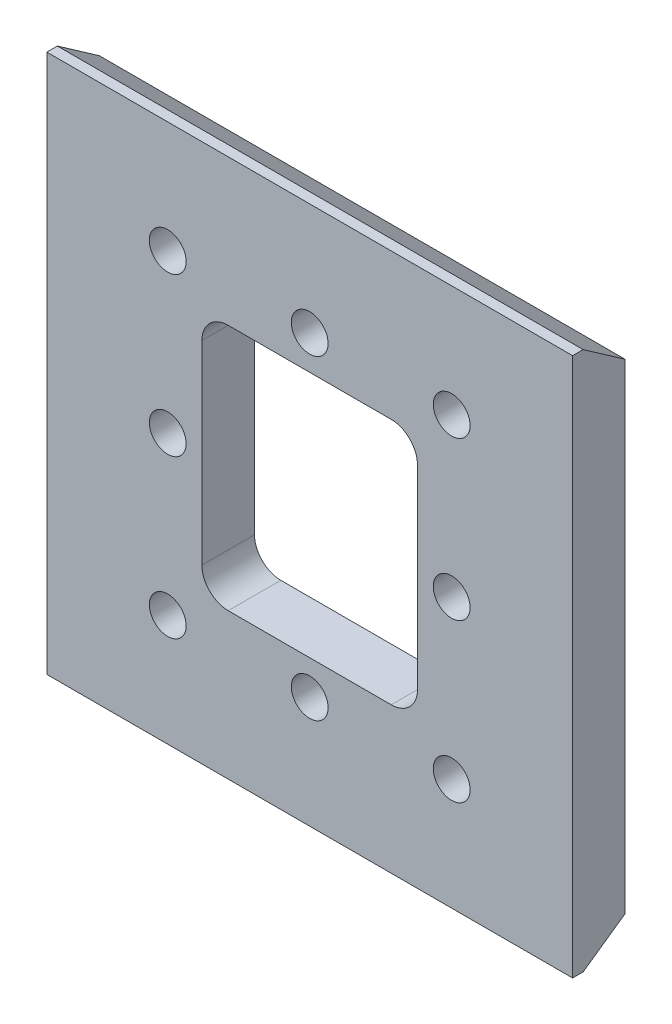
SolidWorks part; units mm, degrees
ref_plane "前视基准面" through (0, 0, 0) normal (0, 0, 1) x (1, 0, 0)
ref_plane "上视基准面" through (0, 0, 0) normal (0, 1, 0) x (1, 0, 0)
ref_plane "右视基准面" through (0, 0, 0) normal (1, 0, 0) x (0, 0, -1)
sketch "草图1" plane through (0, 0, 0) normal (0, 0, 1) x (1, 0, 0)
  line L1 (-100, 102.5) -> (100, 102.5)
  line L2 (-100, 102.5) -> (-100, -102.5)
  line L3 (-100, -102.5) -> (100, -102.5)
  line L4 (100, 102.5) -> (100, -102.5)
  line L5 (-100, 102.5) -> (100, -102.5) construction
  line L6 (-100, -102.5) -> (100, 102.5) construction
  point P0 (0, 0)
  dimension "D1" = 200
  dimension "D2" = 205
extrude "凸台-拉伸1" add sketch "草图1" along normal blind 20
sketch "草图2" plane through (0, 0, 20) normal (0, 0, 1) x (1, 0, 0)
  line L0 (0, 0) -> (128.579, 0) construction
  line L1 (0, 0) -> (0, 91.0919) construction
  line L5 (-31, 47) -> (31, 47)
  line L6 (-41, 37) -> (-41, -37)
  line L7 (-31, -47) -> (31, -47)
  line L8 (41, 37) -> (41, -37)
  line L9 (-41, 47) -> (41, -47) construction
  line L10 (-41, -47) -> (41, 47) construction
  circle A0 centre (-54, 60) radius 7
  circle A1 centre (0, 60) radius 7
  circle A2 centre (-54, 0) radius 7
  circle A3 centre (54, 0) radius 7
  circle A4 centre (54, 60) radius 7
  circle A5 centre (-54, -60) radius 7
  circle A6 centre (0, -60) radius 7
  circle A7 centre (54, -60) radius 7
  arc A8 (-41, -37) -> (-31, -47) centre (-31, -37) ccw
  arc A9 (31, -47) -> (41, -37) centre (31, -37) ccw
  arc A10 (31, 47) -> (41, 37) centre (31, 37) cw
  arc A11 (-31, 47) -> (-41, 37) centre (-31, 37) ccw
  dimension "D1" = 54
  dimension "D2" = 60
  dimension "D3" = 94
  dimension "D5" = 10
  dimension "D6" = 14
  dimension "D7" = 14
  dimension "D8" = 14
  dimension "D4" = 82
extrude "切除-拉伸1" cut sketch "草图2" against normal through all
sketch "草图3" plane through (-100, 0, 0) normal (-1, 0, 0) x (0, 0, 1)
  line L0 (0, 102.5) -> (0, 91.2967)
  line L1 (0, 102.5) -> (0, -102.5) construction
  line L2 (0, 91.2967) -> (16, 102.5)
  line L3 (20, 102.5) -> (0, 102.5) construction
  line L4 (16, 102.5) -> (0, 102.5)
  line L5 (0, -102.5) -> (16, -102.5)
  line L6 (20, -102.5) -> (0, -102.5) construction
  line L7 (16, -102.5) -> (0, -91.2967)
  line L8 (0, -91.2967) -> (0, -102.5)
  dimension "D1" = 16
  dimension "D2" = 35
  dimension "D3" = 35
  dimension "D4" = 16
extrude "切除-拉伸2" cut sketch "草图3" against normal through all
